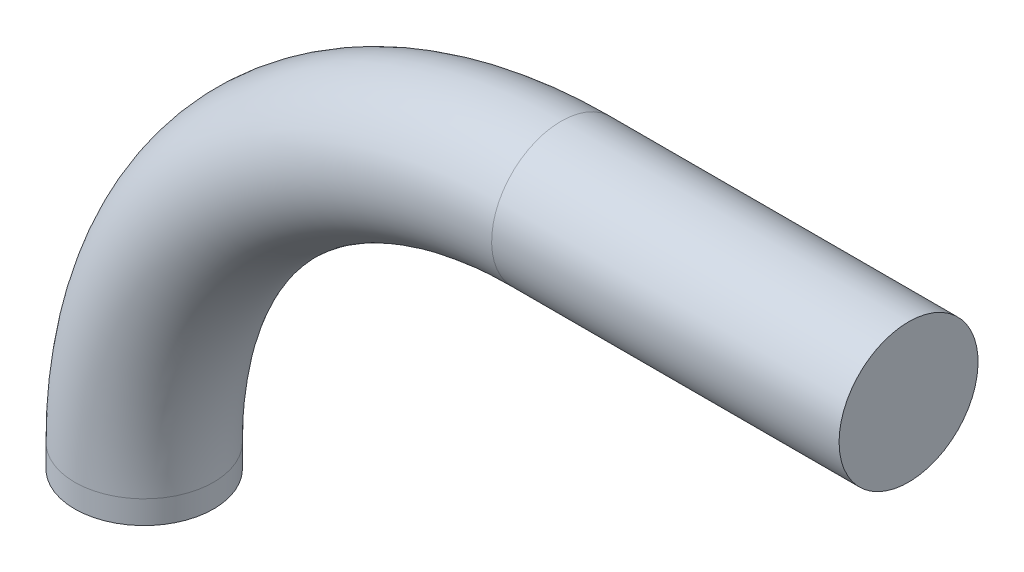
SolidWorks part; units mm, degrees
ref_plane "Front Plane" through (0, 0, 0) normal (0, 0, 1) x (1, 0, 0)
ref_plane "Top Plane" through (0, 0, 0) normal (0, 1, 0) x (1, 0, 0)
ref_plane "Right Plane" through (0, 0, 0) normal (1, 0, 0) x (0, 0, -1)
sketch "Sketch1" plane through (0, 0, 0) normal (0, 0, 1) x (1, 0, 0)
  line L0 (0, 0) -> (0, 1)
  line L1 (18, 19) -> (33, 19)
  arc A0 (0, 1) -> (18, 19) centre (18, 1) cw
  point P6 (0, 19)
  dimension "D3" = 18
  dimension "D1" = 33
  dimension "D2" = 19
  dimension "D4" = 90
sketch "Sketch2" plane through (0, 0, 0) normal (0, 1, 0) x (1, 0, 0)
  circle A0 centre (0, 0) radius 3
  dimension "D1" = 6
sketch "Sketch3" plane through (0, 0, 0) normal (0, 0, 1) x (1, 0, 0)
  circle A0 centre (4, 0) radius 0.5
  dimension "D1" = 1
  dimension "D2" = 4
sweep "Sweep1" add profiles "Sketch2" path "Sketch1"
